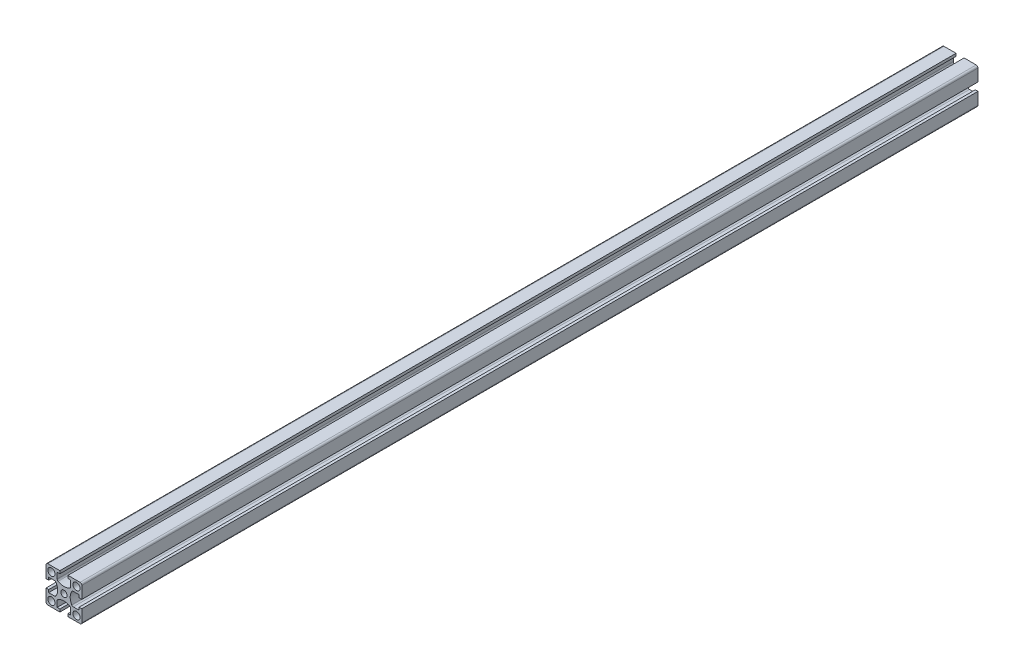
SolidWorks part; units mm, degrees
ref_plane "Front Plane" through (0, 0, 0) normal (0, 0, 1) x (1, 0, 0)
ref_plane "Top Plane" through (0, 0, 0) normal (0, 1, 0) x (1, 0, 0)
ref_plane "Right Plane" through (0, 0, 0) normal (1, 0, 0) x (0, 0, -1)
sketch "Sketch1" plane through (0, 0, 0) normal (0, 0, 1) x (1, 0, 0)
  line L64 (-10, 9) -> (-10, 2.25)
  line L65 (-10, 2.25) -> (-8.5, 2.25)
  line L66 (-8.5, 2.25) -> (-8.5, 3.75)
  line L67 (-8.5, 3.75) -> (-5.2369, 3.75)
  line L68 (-5.2369, -3.75) -> (-8.5, -3.75)
  line L69 (-8.5, -3.75) -> (-8.5, -2.25)
  line L70 (-8.5, -2.25) -> (-10, -2.25)
  line L71 (-10, -2.25) -> (-10, -9)
  line L72 (-9, -10) -> (-2.25, -10)
  line L73 (-2.25, -10) -> (-2.25, -8.5)
  line L74 (-2.25, -8.5) -> (-3.75, -8.5)
  line L75 (-3.75, -8.5) -> (-3.75, -5.2369)
  line L76 (3.75, -5.2369) -> (3.75, -8.5)
  line L77 (3.75, -8.5) -> (2.25, -8.5)
  line L78 (2.25, -8.5) -> (2.25, -10)
  line L79 (2.25, -10) -> (9, -10)
  line L80 (10, -9) -> (10, -2.25)
  line L81 (10, -2.25) -> (8.5, -2.25)
  line L82 (8.5, -2.25) -> (8.5, -3.75)
  line L83 (8.5, -3.75) -> (5.2369, -3.75)
  line L84 (5.2369, 3.75) -> (8.5, 3.75)
  line L85 (8.5, 3.75) -> (8.5, 2.25)
  line L86 (8.5, 2.25) -> (10, 2.25)
  line L87 (10, 2.25) -> (10, 9)
  line L88 (9, 10) -> (2.25, 10)
  line L89 (2.25, 10) -> (2.25, 8.5)
  line L90 (2.25, 8.5) -> (3.75, 8.5)
  line L91 (3.75, 8.5) -> (3.75, 5.2369)
  line L92 (-3.75, 5.2369) -> (-3.75, 8.5)
  line L93 (-3.75, 8.5) -> (-2.25, 8.5)
  line L94 (-2.25, 8.5) -> (-2.25, 10)
  line L95 (-2.25, 10) -> (-9, 10)
  circle A5 centre (-7, -7) radius 2
  circle A6 centre (7, -7) radius 2
  circle A7 centre (7, 7) radius 2
  circle A8 centre (0, 0) radius 1.75
  circle A9 centre (-7, 7) radius 2
  arc A32 (-9, 10) -> (-10, 9) centre (-9, 9) ccw
  arc A33 (-4.3708, 3.25) -> (-5.2369, 3.75) centre (-5.2369, 2.75) ccw
  arc A34 (-4.3708, -3.25) -> (-4.3708, 3.25) centre (-10, 0) ccw
  arc A35 (-5.2369, -3.75) -> (-4.3708, -3.25) centre (-5.2369, -2.75) ccw
  arc A36 (-10, -9) -> (-9, -10) centre (-9, -9) ccw
  arc A37 (-3.25, -4.3708) -> (-3.75, -5.2369) centre (-2.75, -5.2369) ccw
  arc A38 (3.25, -4.3708) -> (-3.25, -4.3708) centre (0, -10) ccw
  arc A39 (3.75, -5.2369) -> (3.25, -4.3708) centre (2.75, -5.2369) ccw
  arc A40 (9, -10) -> (10, -9) centre (9, -9) ccw
  arc A41 (4.3708, -3.25) -> (5.2369, -3.75) centre (5.2369, -2.75) ccw
  arc A42 (4.3708, 3.25) -> (4.3708, -3.25) centre (10, 0) ccw
  arc A43 (5.2369, 3.75) -> (4.3708, 3.25) centre (5.2369, 2.75) ccw
  arc A44 (10, 9) -> (9, 10) centre (9, 9) ccw
  arc A45 (3.25, 4.3708) -> (3.75, 5.2369) centre (2.75, 5.2369) ccw
  arc A46 (-3.25, 4.3708) -> (3.25, 4.3708) centre (0, 10) ccw
  arc A47 (-3.75, 5.2369) -> (-3.25, 4.3708) centre (-2.75, 5.2369) ccw
extrude "Boss-Extrude1" add sketch "Sketch1" along normal blind 500
